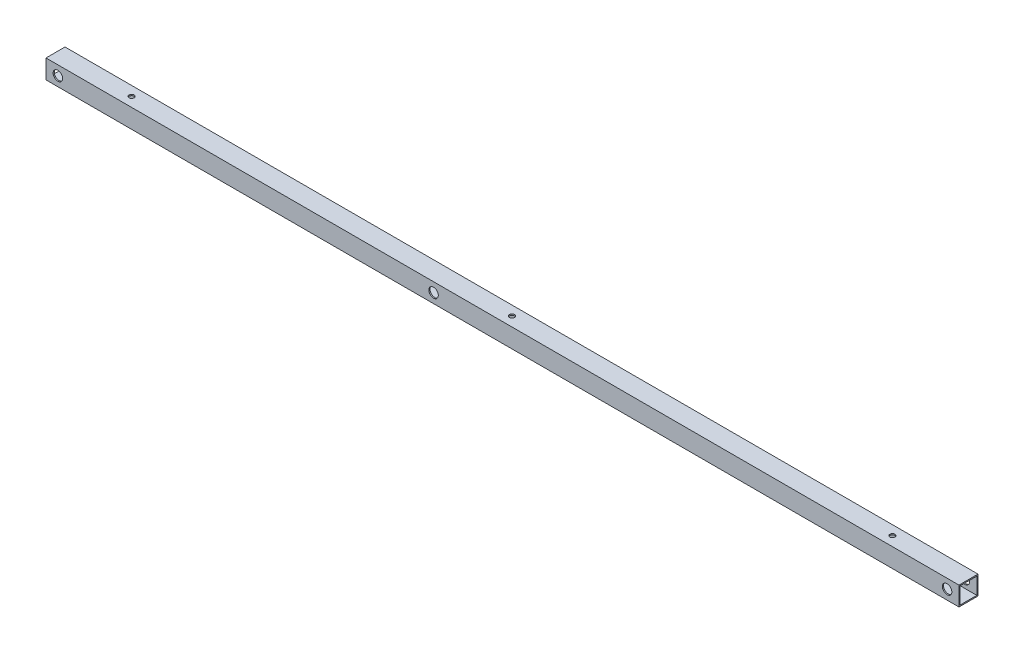
SolidWorks part; units mm, degrees
material "6063-O"
ref_plane "Front Plane" through (0, 0, 0) normal (0, 0, 1) x (1, 0, 0)
ref_plane "Top Plane" through (0, 0, 0) normal (0, 1, 0) x (1, 0, 0)
ref_plane "Right Plane" through (0, 0, 0) normal (1, 0, 0) x (0, 0, -1)
sketch "Sketch1" plane through (0, 0, 0) normal (1, 0, 0) x (0, 0, -1)
  line L1 (-12.7, -12.7) -> (12.7, -12.7)
  line L2 (-12.7, -12.7) -> (-12.7, 12.7)
  line L3 (-12.7, 12.7) -> (12.7, 12.7)
  line L4 (12.7, -12.7) -> (12.7, 12.7)
  line L5 (-12.7, -12.7) -> (12.7, 12.7) construction
  line L6 (-12.7, 12.7) -> (12.7, -12.7) construction
  point P0 (0, 0)
  dimension "D1" = 25.4
extrude "Extrude-Thin1" add sketch "Sketch1" along normal mid plane 1219.2 thin
hole_wizard "1/2 (0.5) Diameter Hole1" positions "Sketch2" profile "Sketch3" hole size "1/2" standard "ANSI Inch"
sketch "Sketch2" plane through (0, 0, 12.7) normal (0, 0, 1) x (1, 0, 0)
  line L0 (13.97, 0) -> (-13.97, 0) construction
  line L1 (609.6, 12.7) -> (609.6, -12.7) construction
  line L2 (-609.6, 12.7) -> (-609.6, -12.7) construction
  point P0 (-593.725, 0)
  point P4 (593.725, 0)
  point P10 (-92.075, 0)
  dimension "D1" = 15.875
  dimension "D2" = 15.875
  dimension "D3" = 685.8
sketch "Sketch3" plane through (-593.725, 0, 12.7) normal (1, 0, 0) x (0, -1, 0)
  line L0 (0, 0) -> (0, 25.4)
  line L1 (0, 25.4) -> (6.35, 25.4)
  line L2 (6.35, 25.4) -> (6.35, 0)
  line L5 (6.35, 0) -> (0, 0)
  line L11 (0, -6.35) -> (0, 107.95) construction
  dimension "Thru Hole Dia." = 12.7
  dimension "Thru Hole Depth" = 25.4
hole_wizard "1/4 Clearance Hole1" positions "Sketch6" profile "Sketch5" hole size "1/4" standard "ANSI Inch" end condition through all
sketch "Sketch6" plane through (0, 12.7, 0) normal (0, 1, 0) x (1, 0, 0)
  line L0 (-13.97, 0) -> (13.97, 0) construction
  line L1 (609.6, 12.7) -> (609.6, -12.7) construction
  line L2 (-609.6, 12.7) -> (-609.6, -12.7) construction
  point P0 (-508, 0)
  point P4 (0, 0)
  point P7 (508, 0)
  dimension "D1" = 101.6
  dimension "D2" = 101.6
sketch "Sketch5" plane through (-508, 12.7, 0) normal (1, 0, 0) x (0, 0, 1)
  line L0 (0, 0) -> (0, 25.4)
  line L1 (0, 25.4) -> (3.3782, 25.4)
  line L2 (3.3782, 25.4) -> (3.3782, 0)
  line L5 (3.3782, 0) -> (0, 0)
  line L11 (0, -6.35) -> (0, 107.95) construction
  dimension "Thru Hole Dia." = 6.7564
  dimension "Thru Hole Depth" = 25.4
